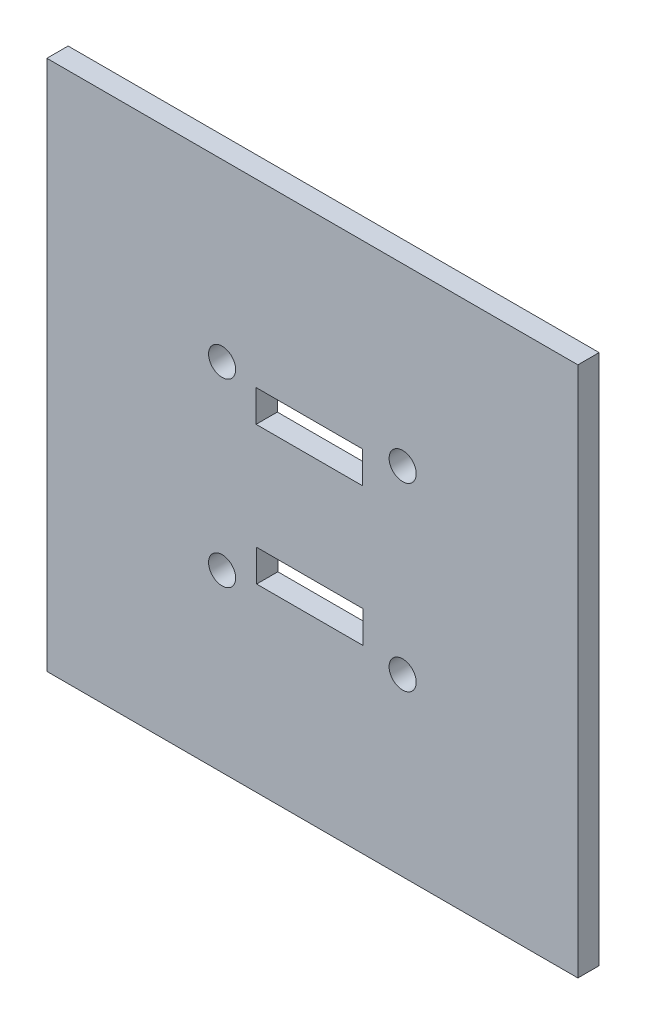
SolidWorks part; units mm, degrees
ref_plane "Front Plane" through (0, 0, 0) normal (0, 0, 1) x (1, 0, 0)
ref_plane "Top Plane" through (0, 0, 0) normal (0, 1, 0) x (1, 0, 0)
ref_plane "Right Plane" through (0, 0, 0) normal (1, 0, 0) x (0, 0, -1)
sketch "Sketch1" plane through (0, 0, 0) normal (0, 0, 1) x (1, 0, 0)
  line L1 (0, 0) -> (50, 0)
  line L2 (0, 0) -> (0, 50)
  line L3 (0, 50) -> (50, 50)
  line L4 (50, 0) -> (50, 50)
  dimension "D1" = 50
  dimension "D2" = 50
extrude "Boss-Extrude1" add sketch "Sketch1" along normal blind 2
sketch "Sketch2" plane through (0, 0, 2) normal (0, 0, 1) x (1, 0, 0)
  line L0 (50, 50) -> (0, 50) construction
  line L1 (0, 50) -> (0, 0) construction
  line L2 (16.5, 33.5) -> (33.5, 33.5) construction
  line L3 (16.5, 33.5) -> (16.5, 16.5) construction
  line L4 (16.5, 16.5) -> (33.5, 16.5) construction
  line L5 (33.5, 33.5) -> (33.5, 16.5) construction
  dimension "D1" = 17
  dimension "D2" = 17
  dimension "D3" = 16.5
  dimension "D4" = 16.5
sketch "Sketch3" plane through (0, 0, 2) normal (0, 0, 1) x (1, 0, 0)
  circle A0 centre (16.5, 33.5) radius 1.275
  circle A1 centre (33.5, 33.5) radius 1.275
  circle A2 centre (33.5, 16.5) radius 1.275
  circle A3 centre (16.5, 16.5) radius 1.275
  dimension "D1" = 2.55
  dimension "D2" = 2
  dimension "D3" = 2
extrude "Cut-Extrude1" cut sketch "Sketch3" against normal up to next
sketch "Sketch4" plane through (0, 0, 2) normal (0, 0, 1) x (1, 0, 0)
  line L0 (50, 50) -> (0, 50) construction
  line L1 (19.7, 33) -> (29.7, 33)
  line L2 (19.7, 33) -> (19.7, 30)
  line L3 (19.7, 30) -> (29.7, 30)
  line L4 (29.7, 33) -> (29.7, 30)
  line L9 (0, 50) -> (0, 0) construction
  line L10 (50, 0) -> (50, 50) construction
  line L11 (19.75, 20) -> (29.75, 20)
  line L12 (19.75, 20) -> (19.75, 17)
  line L13 (19.75, 17) -> (29.75, 17)
  line L14 (29.75, 20) -> (29.75, 17)
  line L15 (0, 0) -> (50, 0) construction
  dimension "D1" = 17
  dimension "D2" = 19.7
  dimension "D3" = 10
  dimension "D4" = 3
  dimension "D5" = 3
  dimension "D6" = 10
  dimension "D7" = 20.25
  dimension "D8" = 17
extrude "Cut-Extrude2" cut sketch "Sketch4" against normal up to next
